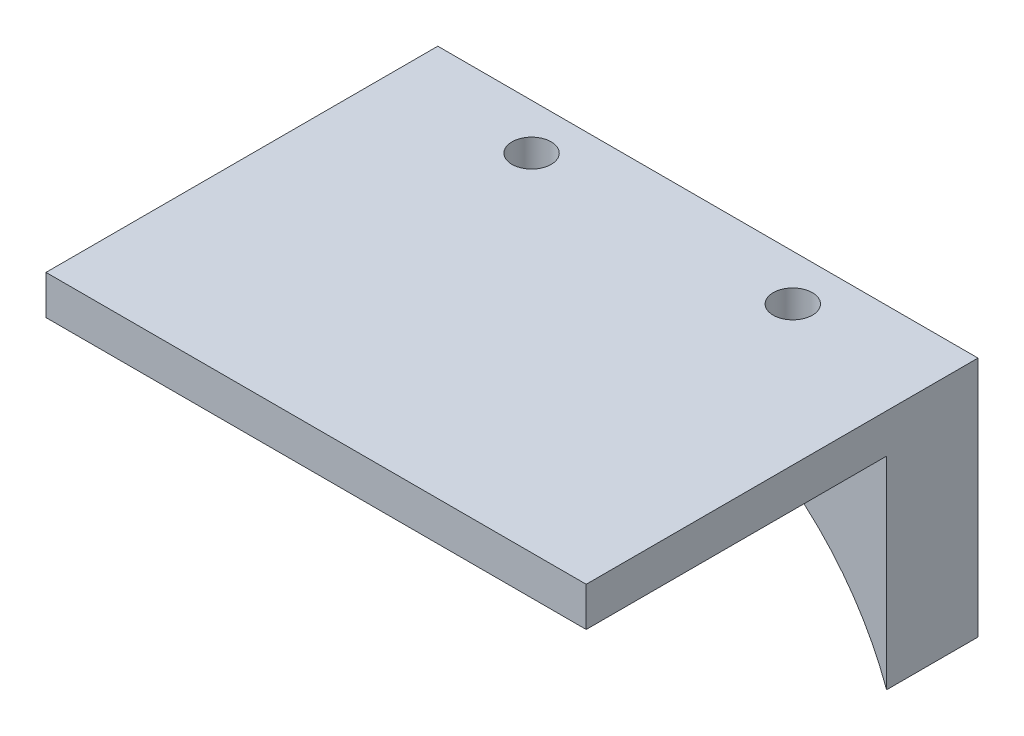
SolidWorks part; units mm, degrees
ref_plane "Front Plane" through (0, 0, 0) normal (0, 0, 1) x (1, 0, 0)
ref_plane "Top Plane" through (0, 0, 0) normal (0, 1, 0) x (1, 0, 0)
ref_plane "Right Plane" through (0, 0, 0) normal (1, 0, 0) x (0, 0, -1)
sketch "Sketch1" plane through (0, 0, 0) normal (0, 0, 1) x (1, 0, 0)
  circle A0 centre (0, 0) radius 22
extrude "Boss-Extrude1" add sketch "Sketch1" along normal blind 7
sketch "Sketch2" plane through (0, 0, 7) normal (0, 0, 1) x (1, 0, 0)
  line L1 (-20.6821, -7.5) -> (20.6821, -7.5)
  line L2 (-20.6821, -7.5) -> (-20.6821, 7.5)
  line L3 (-20.6821, 7.5) -> (20.6821, 7.5)
  line L4 (20.6821, -7.5) -> (20.6821, 7.5)
  line L5 (-20.6821, -7.5) -> (20.6821, 7.5) construction
  line L6 (-20.6821, 7.5) -> (20.6821, -7.5) construction
  circle A0 centre (0, 0) radius 22 construction
  point P0 (0, 0)
  dimension "D1" = 15
extrude "Boss-Extrude2" add sketch "Sketch2" along normal blind 23
sketch "Sketch3" plane through (0, 0, 0) normal (0, 0, -1) x (-1, 0, 0)
  line L3 (-20.6821, 7.5) -> (-20.6821, 26)
  line L4 (-20.6821, 26) -> (20.6821, 26)
  line L5 (20.6821, 26) -> (20.6821, 7.5)
  circle A0 centre (0, 0) radius 22 construction
  arc A1 (-20.6821, 7.5) -> (20.6821, 7.5) centre (0, 0) cw
  point P7 (0, 0)
  circle M5 centre (0, 0) radius 22
  dimension "D1" = 22
  dimension "D3" = 4
extrude "Boss-Extrude3" add sketch "Sketch3" against normal blind 7 separate body contours L5 L4 L3 M5
sketch "Sketch4" plane through (0, 26, 0) normal (0, 1, 0) x (1, 0, 0)
  line L0 (20.6821, -30) -> (-20.6821, -30) construction
  line L1 (-20.6821, -7) -> (20.6821, -7)
  line L2 (-20.6821, -7) -> (-20.6821, -30)
  line L3 (-20.6821, -30) -> (20.6821, -30)
  line L4 (20.6821, -7) -> (20.6821, -30)
  line L5 (20.6821, -7) -> (20.6821, 0) construction
  line L6 (20.6821, -7) -> (-20.6821, -7) construction
extrude "Boss-Extrude4" add sketch "Sketch4" against normal blind 3
sketch "Sketch5" plane through (0, 26, 0) normal (0, 1, 0) x (1, 0, 0)
  line L0 (-20.6821, -7) -> (20.6821, -7) construction
  line L3 (0, 0) -> (0, -7) construction
  line L4 (-10, -3.5) -> (10, -3.5) construction
  circle A0 centre (-10, -3.5) radius 1.5
  circle A1 centre (10, -3.5) radius 1.5
  point P7 (0, -3.5)
  dimension "D1" = 20
extrude "Cut-Extrude1" cut sketch "Sketch5" against normal through all
sketch "Sketch6" plane through (0, 0, 0) normal (0, 0, -1) x (-1, 0, 0)
  circle A0 centre (0, 0) radius 22
extrude "Cut-Extrude2" cut sketch "Sketch6" against normal through all
